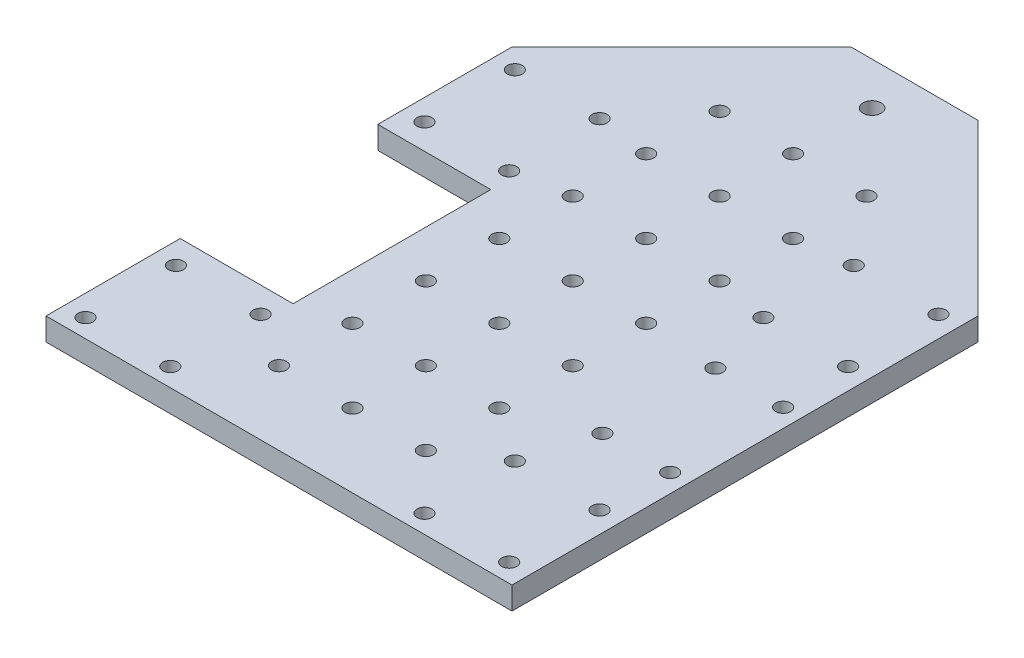
SolidWorks part; units mm, degrees
ref_plane "Front Plane" through (0, 0, 0) normal (0, 0, 1) x (1, 0, 0)
ref_plane "Top Plane" through (0, 0, 0) normal (0, 1, 0) x (1, 0, 0)
ref_plane "Right Plane" through (0, 0, 0) normal (1, 0, 0) x (0, 0, -1)
sketch "Sketch1" plane through (0, 0, 0) normal (0, 1, 0) x (1, 0, 0)
  line L1 (0, 0) -> (165, 0)
  line L2 (0, 0) -> (0, 225)
  line L3 (0, 225) -> (165, 225)
  line L4 (165, 0) -> (165, 225)
  dimension "D1" = 225
  dimension "D2" = 165
extrude "Boss-Extrude1" add sketch "Sketch1" along normal blind 8
sketch "Sketch2" plane through (0, 0, 0) normal (0, -1, 0) x (1, 0, 0)
  line L0 (0, 0) -> (165, 0) construction
  line L1 (0, -225) -> (0, 0) construction
  line L3 (0, -47.5) -> (40, -47.5)
  line L4 (0, -47.5) -> (0, -117.5)
  line L5 (0, -117.5) -> (40, -117.5)
  line L6 (40, -47.5) -> (40, -117.5)
  dimension "D1" = 70
  dimension "D2" = 40
  dimension "D3" = 47.5
extrude "Cut-Extrude1" cut sketch "Sketch2" against normal through all
chamfer "Chamfer1" distance 60 angle 45 2 edges at (165, 4, -225) (0, 4, -225)
hole_wizard "M6 Clearance Hole1" positions "Sketch4" profile "Sketch3" hole size "M6" standard "ISO"
sketch "Sketch4" plane through (0, 8, 0) normal (0, 1, 0) x (1, 0, 0)
  line L0 (105, 225) -> (60, 225) construction
  line L1 (0, -30.2326) -> (0, 30.2326) construction
  point P0 (82.5, 210)
  dimension "D1" = 15
  dimension "D2" = 82.5
sketch "Sketch3" plane through (82.5, 8, -210) normal (1, 0, 0) x (0, 0, 1)
  line L0 (0, 0) -> (0, 9.9228)
  line L1 (0, 9.9228) -> (3.2, 8)
  line L2 (3.2, 8) -> (3.2, 0)
  line L5 (3.2, 0) -> (0, 0)
  line L10 (0, 9.9228) -> (-3.2, 8) construction
  line L11 (0, -6.35) -> (0, 107.95) construction
  dimension "Hole Dia." = 6.4
  dimension "Hole Depth" = 8
  dimension "Drill Angle" = 118
hole_wizard "M5 Clearance Hole1" positions "Sketch7" profile "Sketch5" hole size "M5" standard "ISO"
sketch "Sketch7" plane through (0, 8, 0) normal (0, 1, 0) x (1, 0, 0)
  line L0 (82.5, -51.8738) -> (82.5, 192.9274) construction
  line L2 (-93.1806, 82.5) -> (314.1087, 82.5) construction
  line L4 (-29.3025, 0) -> (29.3025, 0) construction
  line L5 (0, -30.2326) -> (0, 30.2326) construction
  line L6 (0, 165) -> (0, 117.5) construction
  line L8 (7.5, 158.5) -> (37.5, 158.5) construction
  line L9 (37.5, 158.5) -> (37.5, 126.5) construction
  line L10 (37.5, 126.5) -> (7.5, 126.5) construction
  line L12 (134.5, 102.5) -> (158.5, 102.5) construction
  line L14 (165, 0) -> (165, 165) construction
  point P0 (7.5, 158.5)
  point P2 (37.5, 158.5)
  point P4 (37.5, 126.5)
  point P6 (7.5, 126.5)
  point P8 (158.5, 102.5)
  point P10 (134.5, 102.5)
  point P43 (157.5, 126.5)
  point P44 (127.5, 126.5)
  point P45 (127.5, 158.5)
  point P46 (157.5, 158.5)
  point P47 (157.5, 6.5)
  point P48 (127.5, 6.5)
  point P49 (127.5, 38.5)
  point P50 (157.5, 38.5)
  point P51 (134.5, 62.5)
  point P52 (158.5, 62.5)
  point P53 (7.5, 38.5)
  point P54 (37.5, 38.5)
  point P55 (37.5, 6.5)
  point P56 (7.5, 6.5)
  dimension "D1" = 82.5
  dimension "D2" = 82.5
  dimension "D3" = 30
  dimension "D4" = 6.5
  dimension "D5" = 32
  dimension "D6" = 24
  dimension "D7" = 7.5
  dimension "D8" = 6.5
  dimension "D9" = 20
sketch "Sketch5" plane through (7.5, 8, -158.5) normal (1, 0, 0) x (0, 0, 1)
  line L0 (0, 0) -> (0, 9.5923)
  line L1 (0, 9.5923) -> (2.65, 8)
  line L2 (2.65, 8) -> (2.65, 0)
  line L5 (2.65, 0) -> (0, 0)
  line L10 (0, 9.5923) -> (-2.65, 8) construction
  line L11 (0, -6.35) -> (0, 107.95) construction
  dimension "Hole Dia." = 5.3
  dimension "Hole Depth" = 8
  dimension "Drill Angle" = 118
hole_wizard "M5 Clearance Hole2" positions "Sketch9" profile "Sketch8" hole size "M5" standard "ISO"
sketch "Sketch9" plane through (0, 8, 0) normal (0, 1, 0) x (1, 0, 0)
  line L0 (0, -30.2326) -> (0, 30.2326) construction
  line L1 (-29.3025, 0) -> (29.3025, 0) construction
  point P0 (56.5, 26)
  point P18 (82.5, 26)
  point P19 (108.5, 26)
  point P20 (82.5, 52)
  point P21 (108.5, 52)
  point P22 (82.5, 78)
  point P23 (108.5, 78)
  point P24 (82.5, 104)
  point P25 (108.5, 104)
  point P26 (82.5, 130)
  point P27 (108.5, 130)
  point P28 (82.5, 156)
  point P29 (108.5, 156)
  point P30 (82.5, 182)
  point P31 (108.5, 182)
  point P32 (56.5, 52)
  point P33 (56.5, 78)
  point P34 (56.5, 104)
  point P35 (56.5, 130)
  point P36 (56.5, 156)
  point P37 (56.5, 182)
  dimension "D1" = 56.5
  dimension "D2" = 26
  dimension "D3" = 3
  dimension "D4" = 7
sketch "Sketch8" plane through (56.5, 8, -26) normal (1, 0, 0) x (0, 0, 1)
  line L0 (0, 0) -> (0, 9.5923)
  line L1 (0, 9.5923) -> (2.65, 8)
  line L2 (2.65, 8) -> (2.65, 0)
  line L5 (2.65, 0) -> (0, 0)
  line L10 (0, 9.5923) -> (-2.65, 8) construction
  line L11 (0, -6.35) -> (0, 107.95) construction
  dimension "Hole Dia." = 5.3
  dimension "Hole Depth" = 8
  dimension "Drill Angle" = 118
